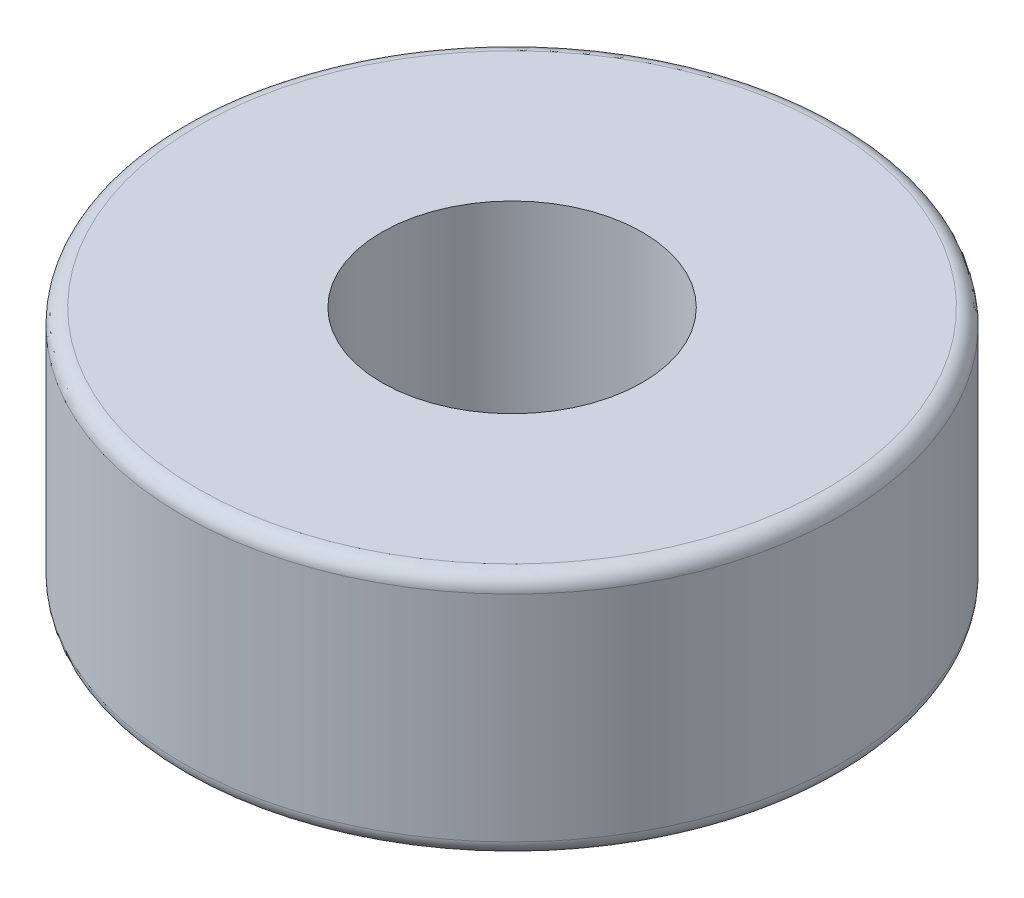
SolidWorks part; units mm, degrees
ref_plane "Front Plane" through (0, 0, 0) normal (0, 0, 1) x (1, 0, 0)
ref_plane "Top Plane" through (0, 0, 0) normal (0, 1, 0) x (1, 0, 0)
ref_plane "Right Plane" through (0, 0, 0) normal (1, 0, 0) x (0, 0, -1)
sketch "Sketch1" plane through (0, 0, 0) normal (0, 1, 0) x (1, 0, 0)
  circle A0 centre (0, 0) radius 10.75
  circle A1 centre (0, 0) radius 4.25
  dimension "D1" = 21.5
  dimension "D2" = 8.5
extrude "Boss-Extrude1" add sketch "Sketch1" along normal blind 8
fillet "Fillet1" radius 0.5 1 edges at (0, 8, 10.75)
fillet "Fillet2" radius 0.5 1 edges at (0, 0, 10.75)
